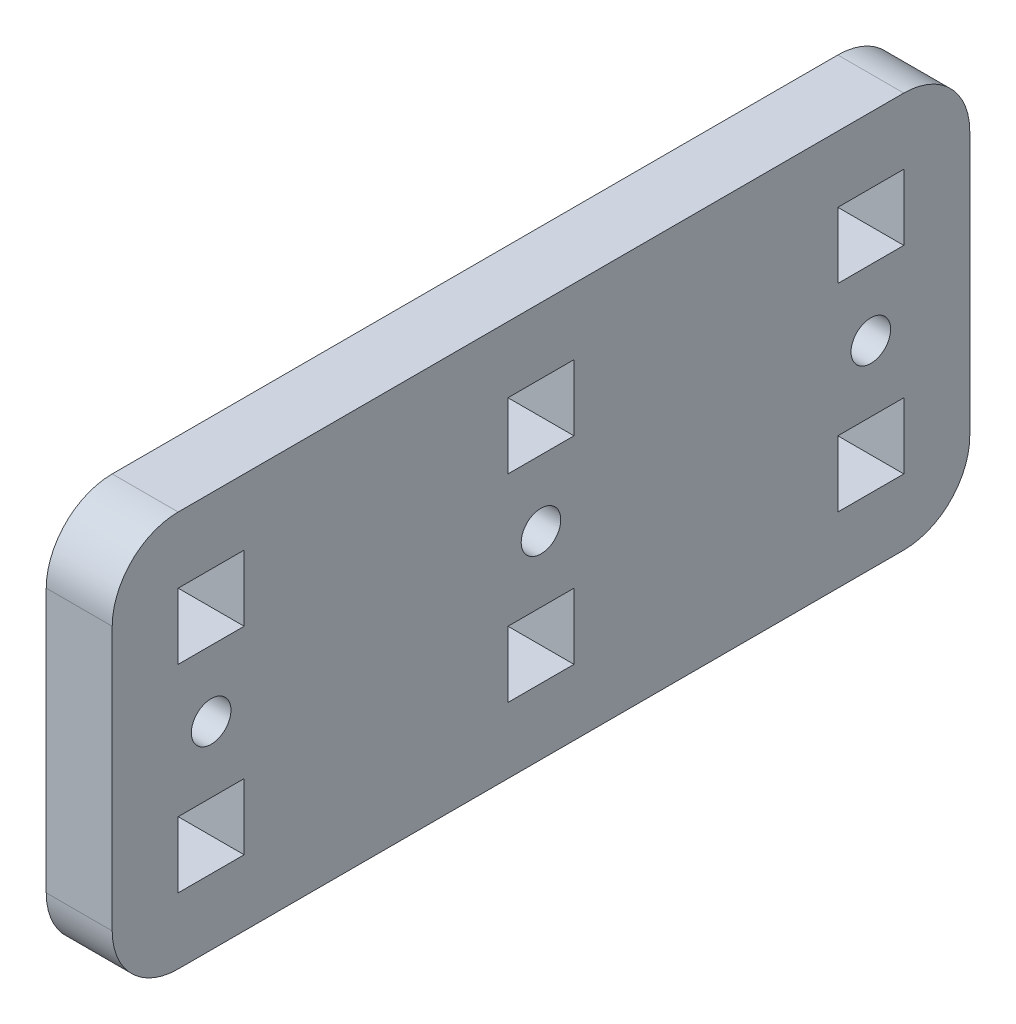
SolidWorks part; units mm, degrees
ref_plane "Front Plane" through (0, 0, 0) normal (0, 0, 1) x (1, 0, 0)
ref_plane "Top Plane" through (0, 0, 0) normal (0, 1, 0) x (1, 0, 0)
ref_plane "Right Plane" through (0, 0, 0) normal (1, 0, 0) x (0, 0, -1)
sketch "Sketch1" plane through (0, 0, 0) normal (1, 0, 0) x (0, 0, -1)
  line L0 (0, 15) -> (65, 15) construction
  line L1 (0, 0) -> (65, 0)
  line L2 (0, 0) -> (0, 30)
  line L3 (0, 30) -> (65, 30)
  line L4 (65, 0) -> (65, 30)
  line L5 (32.5, 30) -> (32.5, 0) construction
  line B0 (7.5, 20) -> (7.5, 10) construction
  line B1 (10, 20) -> (10, 25)
  line B2 (10, 20) -> (5, 20)
  line B3 (5, 20) -> (5, 25)
  line B4 (10, 25) -> (5, 25)
  line B5 (10, 10) -> (10, 5)
  line B6 (10, 10) -> (5, 10)
  line B7 (5, 10) -> (5, 5)
  line B8 (10, 5) -> (5, 5)
  line B9 (7.5, 15) -> (14.4724, 15) construction
  circle B10 centre (7.5, 15) radius 1.5
  line B11 (57.5, 20) -> (57.5, 10) construction
  line B12 (55, 20) -> (55, 25)
  line B13 (55, 20) -> (60, 20)
  line B14 (60, 20) -> (60, 25)
  line B15 (55, 25) -> (60, 25)
  line B16 (55, 10) -> (55, 5)
  line B17 (55, 10) -> (60, 10)
  line B18 (60, 10) -> (60, 5)
  line B19 (55, 5) -> (60, 5)
  circle B20 centre (57.5, 15) radius 1.5
  line B21 (32.5, 20) -> (32.5, 10) construction
  line B22 (30, 20) -> (30, 25)
  line B23 (30, 20) -> (35, 20)
  line B24 (35, 20) -> (35, 25)
  line B25 (30, 25) -> (35, 25)
  line B26 (30, 10) -> (30, 5)
  line B27 (30, 10) -> (35, 10)
  line B28 (35, 10) -> (35, 5)
  line B29 (30, 5) -> (35, 5)
  line B30 (32.5, 15) -> (25.5276, 15) construction
  circle B31 centre (32.5, 15) radius 1.5
  dimension "D1" = 5
  dimension "D2" = 5
  dimension "D3" = 50
sketch_block_instance "Trou M3 plots 5mm-1"
sketch_block "Trou M3 plots 5mm" parameters "D2"=3, "D1"=5, "D3"=5, "D4"=10
sketch_block_instance "Trou M3 plots 5mm-3"
sketch_block_instance "Trou M3 plots 5mm-4"
extrude "Boss-Extrude1" add sketch "Sketch1" along normal blind 5
fillet "Fillet1" radius 5 4 edges at (2.5, 0, -65) (2.5, 30, -65) (2.5, 0, 0) (2.5, 30, 0)
